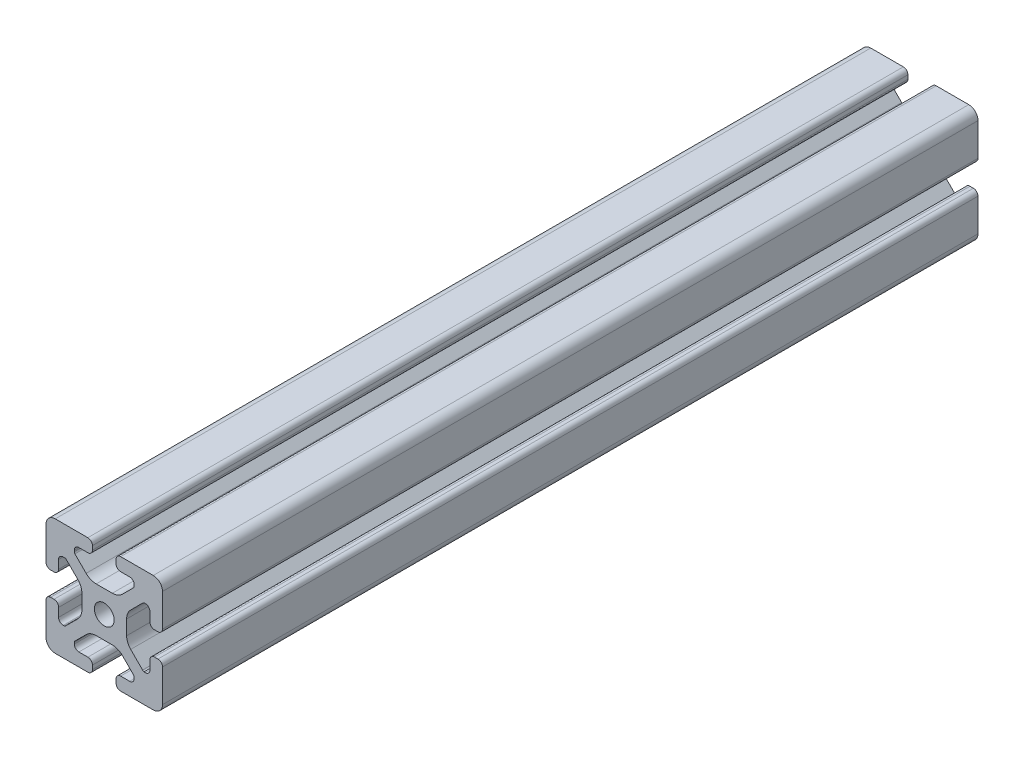
SolidWorks part; units mm, degrees
material "6061 Alloy"
ref_plane "Front Plane" through (0, 0, 0) normal (0, 0, 1) x (1, 0, 0)
ref_plane "Top Plane" through (0, 0, 0) normal (0, 1, 0) x (1, 0, 0)
ref_plane "Right Plane" through (0, 0, 0) normal (1, 0, 0) x (0, 0, -1)
sketch "Sketch1" plane through (0, 0, 0) normal (0, 0, 1) x (1, 0, 0)
  line L0 (0, 19.7407) -> (0, -19.7407) construction
  line L1 (19.0335, 0) -> (-20.7246, 0) construction
  line L2 (-8.715, -15.5246) -> (-5.63, -15.5246)
  line L3 (-10.285, -13.9546) -> (-10.285, -13.4925)
  line L4 (-6.2171, -9.1098) -> (-10.0624, -12.9551)
  line L5 (2.7773, -7.685) -> (-2.7773, -7.685)
  line L6 (10.0624, -12.9551) -> (6.2171, -9.1098)
  line L7 (10.285, -13.9546) -> (10.285, -13.4925)
  line L8 (5.63, -15.5246) -> (8.715, -15.5246)
  line L9 (4.06, -18.43) -> (4.06, -17.0946)
  line L10 (-4.06, -18.43) -> (-4.06, -17.0946)
  line L11 (15.68, -8.7154) -> (15.68, -5.63)
  line L12 (-14.11, -10.2854) -> (-13.8169, -10.2854)
  line L13 (20, -16.83) -> (20, -5.63)
  line L14 (20, 5.63) -> (20, 13.0011)
  line L15 (-16.83, 20) -> (-5.63, 20)
  line L16 (5.63, 20) -> (12.9796, 20)
  line L18 (-8.715, 15.5246) -> (-5.63, 15.5246)
  line L19 (-20, -17.0184) -> (-20, -5.7579)
  line L20 (-20, 5.573) -> (-20, 13.0045)
  line L21 (-15.68, -8.7154) -> (-15.68, -5.7579)
  line L23 (-16.6746, -20) -> (-5.63, -20)
  line L24 (5.63, -20) -> (13, -20)
  line L53 (14.11, -10.2854) -> (13.6201, -10.2854)
  line L54 (13.1637, -9.947) -> (9.0762, -5.8595)
  line L55 (7.685, -2.5008) -> (7.685, 2.5008)
  line L56 (9.0762, 5.8595) -> (13.2795, 10.0628)
  line L57 (13.8169, 10.2854) -> (14.11, 10.2854)
  line L58 (15.68, 8.7154) -> (15.68, 5.63)
  line L59 (17.25, 4.06) -> (18.43, 4.06)
  line L61 (20, 13.0011) -> (20, 16.83)
  line L62 (16.83, 20) -> (12.9796, 20)
  line L64 (4.06, 18.43) -> (4.06, 17.0946)
  line L65 (5.63, 15.5246) -> (8.715, 15.5246)
  line L66 (10.285, 13.9546) -> (10.285, 13.4925)
  line L67 (10.0624, 12.9551) -> (6.2171, 9.1098)
  line L68 (2.7773, 7.685) -> (-2.7773, 7.685)
  line L69 (-6.2171, 9.1098) -> (-10.0624, 12.9551)
  line L70 (-10.285, 13.4925) -> (-10.285, 13.9546)
  line L72 (-4.06, 17.0946) -> (-4.06, 18.43)
  line L75 (-20, 16.83) -> (-20, 13.0045)
  line L77 (-18.43, 4.003) -> (-17.25, 4.003)
  line L78 (-15.68, 5.573) -> (-15.68, 8.4757)
  line L79 (-14.0552, 10.0447) -> (-13.7199, 10.033)
  line L80 (-13.0405, 9.8238) -> (-9.0762, 5.8595)
  line L81 (-7.685, 2.5008) -> (-7.685, -2.5008)
  line L82 (-9.0762, -5.8595) -> (-13.2795, -10.0628)
  line L85 (-17.25, -4.1204) -> (-18.43, -4.1204)
  line L100 (13, -20) -> (16.83, -20)
  line L103 (18.43, -4.06) -> (17.25, -4.06)
  arc A0 (-5.63, -15.5246) -> (-4.06, -17.0946) centre (-5.63, -17.0946) cw
  arc A1 (-8.715, -15.5246) -> (-10.285, -13.9546) centre (-8.715, -13.9546) cw
  arc A2 (-10.285, -13.4925) -> (-10.0624, -12.9551) centre (-9.525, -13.4925) cw
  arc A3 (-6.2171, -9.1098) -> (-2.7773, -7.685) centre (-2.7773, -12.5496) cw
  arc A4 (2.7773, -7.685) -> (6.2171, -9.1098) centre (2.7773, -12.5496) cw
  arc A5 (10.0624, -12.9551) -> (10.285, -13.4925) centre (9.525, -13.4925) cw
  arc A6 (10.285, -13.9546) -> (8.715, -15.5246) centre (8.715, -13.9546) cw
  arc A7 (4.06, -17.0946) -> (5.63, -15.5246) centre (5.63, -17.0946) cw
  arc A8 (5.63, -20) -> (4.06, -18.43) centre (5.63, -18.43) cw
  arc A9 (-4.06, -18.43) -> (-5.63, -20) centre (-5.63, -18.43) cw
  circle A45 centre (0, 0) radius 3.4
  arc A46 (17.25, -4.06) -> (15.68, -5.63) centre (17.25, -5.63) ccw
  arc A47 (14.11, -10.2854) -> (15.68, -8.7154) centre (14.11, -8.7154) ccw
  arc A48 (13.1637, -9.947) -> (13.6201, -10.2854) centre (13.8117, -9.55) ccw
  arc A49 (7.685, -2.5008) -> (9.0762, -5.8595) centre (12.435, -2.5008) ccw
  arc A50 (9.0762, 5.8595) -> (7.685, 2.5008) centre (12.435, 2.5008) ccw
  arc A51 (13.8169, 10.2854) -> (13.2795, 10.0628) centre (13.8169, 9.5254) ccw
  arc A52 (15.68, 8.7154) -> (14.11, 10.2854) centre (14.11, 8.7154) ccw
  arc A53 (15.68, 5.63) -> (17.25, 4.06) centre (17.25, 5.63) ccw
  arc A54 (18.43, 4.06) -> (20, 5.63) centre (18.43, 5.63) ccw
  arc A55 (20, 16.83) -> (16.83, 20) centre (16.83, 16.83) ccw
  arc A56 (5.63, 20) -> (4.06, 18.43) centre (5.63, 18.43) ccw
  arc A57 (4.06, 17.0946) -> (5.63, 15.5246) centre (5.63, 17.0946) ccw
  arc A58 (10.285, 13.9546) -> (8.715, 15.5246) centre (8.715, 13.9546) ccw
  arc A59 (10.0624, 12.9551) -> (10.285, 13.4925) centre (9.525, 13.4925) ccw
  arc A60 (2.7773, 7.685) -> (6.2171, 9.1098) centre (2.7773, 12.5496) ccw
  arc A61 (-6.2171, 9.1098) -> (-2.7773, 7.685) centre (-2.7773, 12.5496) ccw
  arc A62 (-10.285, 13.4925) -> (-10.0624, 12.9551) centre (-9.525, 13.4925) ccw
  arc A63 (-8.715, 15.5246) -> (-10.285, 13.9546) centre (-8.715, 13.9546) ccw
  arc A64 (-5.63, 15.5246) -> (-4.06, 17.0946) centre (-5.63, 17.0946) ccw
  arc A65 (-4.06, 18.43) -> (-5.63, 20) centre (-5.63, 18.43) ccw
  arc A66 (-16.83, 20) -> (-20, 16.83) centre (-16.83, 16.83) ccw
  arc A67 (-20, 5.573) -> (-18.43, 4.003) centre (-18.43, 5.573) ccw
  arc A68 (-17.25, 4.003) -> (-15.68, 5.573) centre (-17.25, 5.573) ccw
  arc A69 (-14.0552, 10.0447) -> (-15.68, 8.4757) centre (-14.11, 8.4757) ccw
  arc A70 (-13.0405, 9.8238) -> (-13.7199, 10.033) centre (-13.5779, 9.2864) ccw
  arc A71 (-7.685, 2.5008) -> (-9.0762, 5.8595) centre (-12.435, 2.5008) ccw
  arc A72 (-9.0762, -5.8595) -> (-7.685, -2.5008) centre (-12.435, -2.5008) ccw
  arc A73 (-13.8169, -10.2854) -> (-13.2795, -10.0628) centre (-13.8169, -9.5254) ccw
  arc A74 (-15.68, -8.7154) -> (-14.11, -10.2854) centre (-14.11, -8.7154) ccw
  arc A75 (-15.68, -5.7579) -> (-17.25, -4.1204) centre (-17.2485, -5.6904) ccw
  arc A76 (-18.43, -4.1204) -> (-20, -5.7579) centre (-18.4315, -5.6904) ccw
  arc A77 (-20, -17.0184) -> (-16.6746, -20) centre (-16.8354, -16.8341) ccw
  arc A88 (16.83, -20) -> (20, -16.83) centre (16.83, -16.83) ccw
  arc A89 (20, -5.63) -> (18.43, -4.06) centre (18.43, -5.63) ccw
  dimension "D2" = 6.8
  dimension "D7" = 20.57
  dimension "D1" = 40
  dimension "D3" = 4.32
  dimension "D4" = 15.37
  dimension "D5" = 20
  dimension "D6" = 4.32
  dimension "D9" = 15.37
extrude "Extrude1" add sketch "Sketch1" against normal blind 280
equation "\"PinDiameter\"= 0"
equation "\"WallThickness\"= 0.5cm"
equation "\"BottomPlateX\"= 100cm"
equation "\"BottomPlateZ\"= 70cm"
equation "\"BottomPlateHoleD\"=((\"ArmPlateX\")^2+(\"ArmPlateDepth\")^2)^.5+ 10mm"
equation "\"ActuatorL\"= 35cm"
equation "\"ActuatorPinD\"= 6.35mm"
equation "\"ActuatorPinL\"= 15cm"
equation "\"Box-X\"= 40cm"
equation "\"Box-Z\"= 20cm"
equation "\"Box-Y\"= 30cm"
equation "\"ArmPlateThickness\"= 1cm"
equation "\"ArmPlateX\"= 50cm"
equation "\"ArmPlateDepth\"= 20cm"
equation "\"Arm1X\"= 5cm"
equation "\"Arm1L\"= 60cm"
equation "\"Arm2GAP\"= 5cm"
equation "\"Arm2L\"= 60cm"
equation "\"Arm2H\"= 5cm"
equation "\"Arm2Extension\"= 5cm"
equation "\"Arm3GAP\"= 5cm"
equation "\"Arm3L\"= 60cm"
equation "\"Arm3H\"= 5cm"
equation "\"Pin1-2L\"= \"Arm2GAP\" + (2 * \"WallThickness\")"
equation "\"Pin2-3L\"= \"Arm3GAP\" + (4 * \"WallThickness\")"
equation "\"DCMotor1D\"= 65mm"
equation "\"DCMotor1L\"= 215mm"
equation "\"DCMotor1ShaftL\"= 30mm"
equation "\"DCMotor2X\"= 68mm"
equation "\"DCMotor2D\"= 65mm"
equation "\"DCMotor2L\"= 215mm"
equation "\"DCMotor2ShaftL\"= 30mm"
equation "\"DCMotor2ShaftD\"= 15mm"
equation "\"BenchDepth\"= 5cm"
equation "\"BenchH\"= 10cm"
equation "\"BenchL\"= 15cm"
equation "\"PillowBlockW\"= 5cm"
equation "\"PillowBlockCenterH\"= \"DCMotor2X\"/2"
equation "\"EncoderRadius\"= 19mm"
equation "\"EncoderShaftL\"= 15mm"
equation "\"EncoderL\"= 33mm"
equation "\"EncoderHousingThickness\"= 7.5mm"
equation "\"TurntableID\"= 70mm"
equation "\"TurntableInner2*t\" = (\"TurntableOD\"-\"TurntableID\")*.25 - .5mm"
equation "\"TurntableInnerHoleRadius\"= \"TurntableID\"*.5 + \"TurntableInner2*t\"*.5"
equation "\"TurntableOD\"= 120mm"
equation "\"TurntableOuterHoleRadius\" = \"TurntableOD\"*.5 - ((\"TurntableOD\"-\"TurntableID\")*.25-.5mm)*.5"
equation "\"4040Height\" = 30cm"
equation "\"LENGTH@Extrude1\"=\"4040Height\"-20mm"
